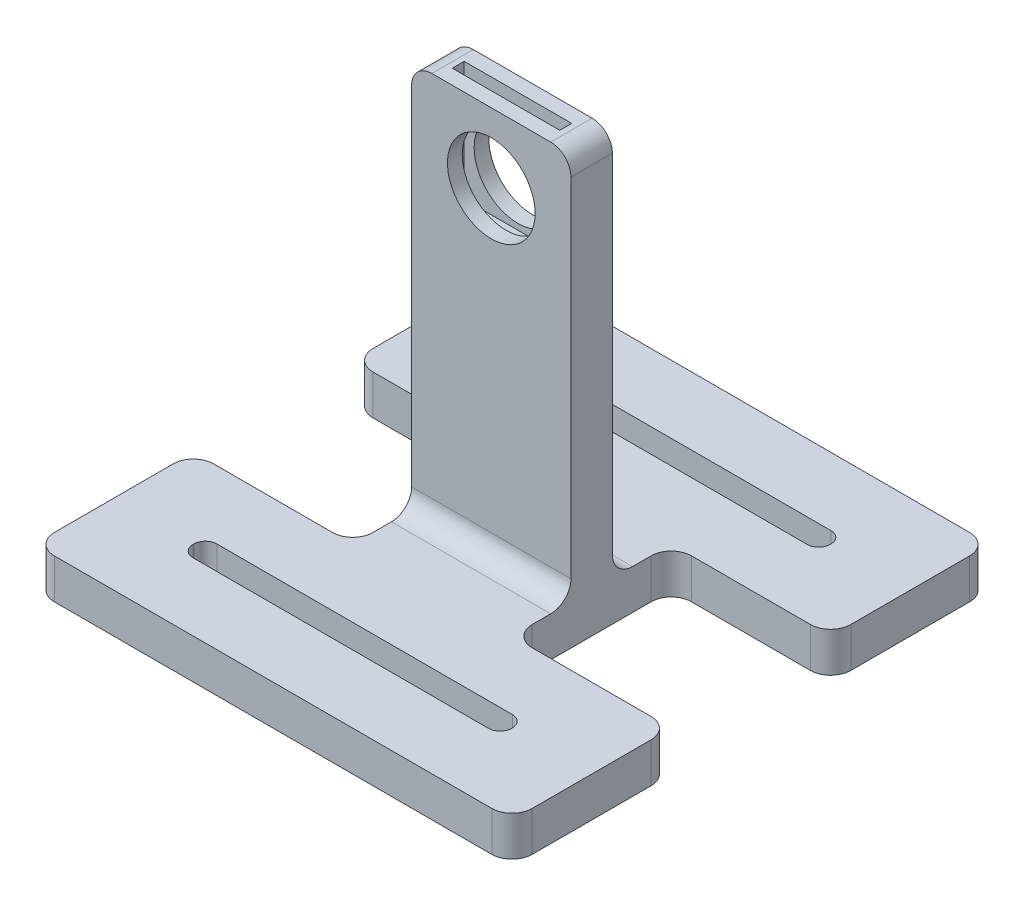
SolidWorks part; units mm, degrees
ref_plane "Front Plane" through (0, 0, 0) normal (0, 0, 1) x (1, 0, 0)
ref_plane "Top Plane" through (0, 0, 0) normal (0, 1, 0) x (1, 0, 0)
ref_plane "Right Plane" through (0, 0, 0) normal (1, 0, 0) x (0, 0, -1)
sketch "Sketch1" plane through (0, 0, 0) normal (0, 1, 0) x (1, 0, 0)
  line L1 (-30, -30) -> (30, -30)
  line L2 (-30, -30) -> (-30, -10)
  line L3 (-30, 30) -> (30, 30)
  line L4 (30, -30) -> (30, -9.7107)
  line L10 (-30, 10) -> (-10, 10)
  line L11 (-30, 30) -> (-30, 10)
  line L12 (30, 30) -> (30, 10)
  line L13 (30, 10) -> (10, 10)
  line L14 (10, 10) -> (10, -10)
  line L15 (10, -10) -> (30, -10)
  line L16 (-10, 10) -> (-10, -10)
  line L17 (-10, -10) -> (-30, -10)
  point P0 (0, 0)
  dimension "D1" = 60
  dimension "D2" = 60
  dimension "D4" = 20
  dimension "D5" = 20
extrude "Boss-Extrude1" add sketch "Sketch1" along normal blind 5 contours L16 L17 L2 L1 L4 L15 L14 L13 L12 L3 L11 L10
sketch "Sketch2" plane through (0, 5, 0) normal (0, 1, 0) x (1, 0, 0)
  line L0 (-30, 20) -> (30, 20) construction
  line L1 (-30, 30) -> (-30, 10) construction
  line L2 (30, 30) -> (30, 10) construction
  line L3 (-20, 10) -> (-20, 30) construction
  line L4 (-30, 10) -> (-10, 10) construction
  line L5 (-30, 30) -> (30, 30) construction
  line L6 (20, 10) -> (20, 30) construction
  line L7 (30, 10) -> (10, 10) construction
  line L8 (-30, -20) -> (30, -20) construction
  line L9 (-30, -30) -> (-30, -10) construction
  line L10 (30, -30) -> (30, -10) construction
  line L11 (20, -10) -> (20, -30) construction
  line L12 (10, -10) -> (30, -10) construction
  line L13 (-30, -30) -> (30, -30) construction
  line L14 (-20, -10) -> (-20, -30) construction
  line L15 (-10, -10) -> (-30, -10) construction
  line L17 (-18.55, 18.5) -> (18.55, 18.5)
  line L18 (-20, 19.95) -> (-20, 20.05)
  line L19 (-18.55, 21.5) -> (18.55, 21.5)
  line L20 (20, 19.95) -> (20, 20.05)
  line L21 (-20, 18.5) -> (20, 21.5) construction
  line L22 (-20, 21.5) -> (20, 18.5) construction
  line L23 (-18.55, -21.5) -> (18.55, -21.5)
  line L24 (-20, -20.05) -> (-20, -19.95)
  line L25 (-18.55, -18.5) -> (18.55, -18.5)
  line L26 (20, -20.05) -> (20, -19.95)
  line L27 (-20, -21.5) -> (20, -18.5) construction
  line L28 (-20, -18.5) -> (20, -21.5) construction
  arc A0 (-18.55, -21.5) -> (-20, -20.05) centre (-18.55, -20.05) cw
  arc A1 (-20, -19.95) -> (-18.55, -18.5) centre (-18.55, -19.95) cw
  arc A2 (18.55, -21.5) -> (20, -20.05) centre (18.55, -20.05) ccw
  arc A3 (18.55, -18.5) -> (20, -19.95) centre (18.55, -19.95) cw
  arc A4 (18.55, 18.5) -> (20, 19.95) centre (18.55, 19.95) ccw
  arc A5 (-18.55, 18.5) -> (-20, 19.95) centre (-18.55, 19.95) cw
  arc A6 (18.55, 21.5) -> (20, 20.05) centre (18.55, 20.05) cw
  arc A7 (-20, 20.05) -> (-18.55, 21.5) centre (-18.55, 20.05) cw
  point P32 (0, 20)
  point P37 (0, -20)
  dimension "D3" = 1.45
  dimension "D1" = 3
  dimension "D2" = 3
extrude "Cut-Extrude1" cut sketch "Sketch2" against normal through all
fillet "Fillet1" radius 2.54 12 edges at (-30, 2.5, -30) (-30, 2.5, -10) (-10, 2.5, -10) (-10, 2.5, 10) (-30, 2.5, 10) (-30, 2.5, 30) (30, 2.5, 30) (30, 2.5, 10) (10, 2.5, 10) (10, 2.5, -10) (30, 2.5, -10) (30, 2.5, -30)
sketch "Sketch3" plane through (0, 5, 0) normal (0, 1, 0) x (1, 0, 0)
  line L1 (-10, 10) -> (10, 10)
  line L2 (-10, 10) -> (-10, -10)
  line L3 (-10, -10) -> (10, -10)
  line L4 (10, 10) -> (10, -10)
  line L5 (-10, 10) -> (10, -10) construction
  line L6 (-10, -10) -> (10, 10) construction
  point P0 (0, 0)
  dimension "D1" = 20
  dimension "D2" = 20
sketch "Sketch9" plane through (0, 5, 0) normal (0, 1, 0) x (1, 0, 0)
  line L0 (10, 10) -> (10, -10) construction
  line L1 (-10, -2.6005) -> (10, -2.6005)
  line L2 (-10, -2.6005) -> (-10, 2.6005)
  line L3 (-10, 2.6005) -> (10, 2.6005)
  line L4 (10, -2.6005) -> (10, 2.6005)
  line L5 (-10, -2.6005) -> (10, 2.6005) construction
  line L6 (-10, 2.6005) -> (10, -2.6005) construction
  point P0 (0, 0)
  dimension "D1" = 5.201
extrude "Boss-Extrude5" add sketch "Sketch9" along normal blind 33.75
sketch "Sketch11" plane through (0, 38.75, 0) normal (0, 1, 0) x (1, 0, 0)
  line L0 (10, 10) -> (10, -10) construction
  line L1 (-10, -0.75) -> (10, -0.75)
  line L2 (-10, -0.75) -> (-10, 0.75)
  line L3 (-10, 0.75) -> (10, 0.75)
  line L4 (10, -0.75) -> (10, 0.75)
  line L5 (-10, -0.75) -> (10, 0.75) construction
  line L6 (-10, 0.75) -> (10, -0.75) construction
  line L7 (-10, 10) -> (10, -10) construction
  line L8 (-6.75, -0.75) -> (6.75, -0.75)
  line L9 (-6.75, -0.75) -> (-6.75, 0.75)
  line L10 (-6.75, 0.75) -> (6.75, 0.75)
  line L11 (6.75, -0.75) -> (6.75, 0.75)
  line L12 (-6.75, -0.75) -> (6.75, 0.75) construction
  line L13 (-6.75, 0.75) -> (6.75, -0.75) construction
  point P0 (0, 0)
  point P8 (0, 0)
  line M4 (10, -2.6005) -> (10, 2.6005)
  line M5 (10, 2.6005) -> (-10, 2.6005)
  line M6 (-10, 2.6005) -> (-10, -2.6005)
  line M7 (-10, -2.6005) -> (10, -2.6005)
  dimension "D1" = 1.5
  dimension "D2" = 13.5
extrude "Boss-Extrude6" add sketch "Sketch11" along normal blind 15 contours L3 M6 M4 M5 | L1 L9 L3 M6 | L1 M6 M7 M4 | L11 L1 L3 M4
sketch "Sketch12" plane through (0, 0, 2.6005) normal (0, 0, 1) x (1, 0, 0)
  line L0 (-10, 38.75) -> (10, 38.75) construction
  line L1 (-10, 53.75) -> (-10, 5) construction
  line L2 (10, 53.75) -> (10, 5) construction
  line L3 (-10, 53.75) -> (10, 53.75) construction
  line L4 (-10, 51.25) -> (10, 51.25) construction
  line L5 (0, 51.25) -> (0, 38.75) construction
  circle A0 centre (0, 45) radius 5.5
  dimension "D3" = 11
  dimension "D1" = 15
  dimension "D2" = 12.5
extrude "Cut-Extrude3" cut sketch "Sketch12" against normal through all
fillet "Fillet3" radius 2.54 4 edges at (10, 53.75, 0) (-10, 53.75, 0) (0, 5, 2.6005) (0, 5, -2.6005)
